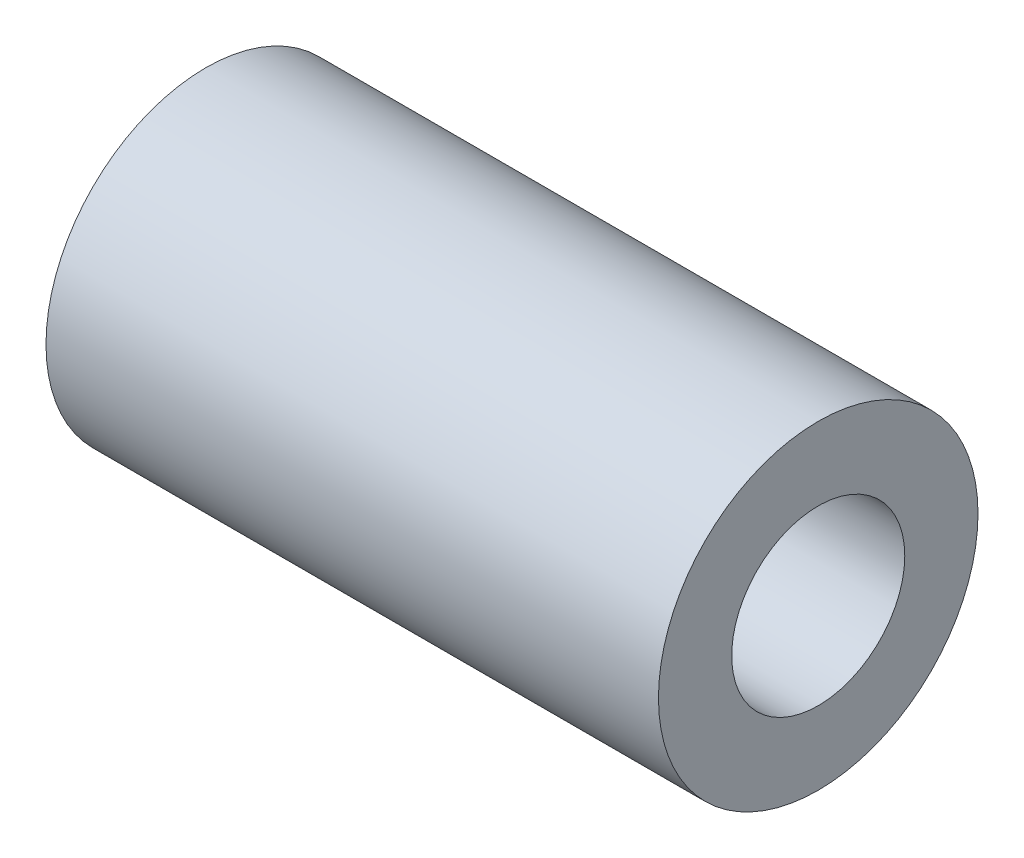
SolidWorks part; units mm, degrees
material "Nylon 101"
ref_plane "Спереди" through (0, 0, 0) normal (0, 0, 1) x (1, 0, 0)
ref_plane "Сверху" through (0, 0, 0) normal (0, 1, 0) x (1, 0, 0)
ref_plane "Справа" through (0, 0, 0) normal (1, 0, 0) x (0, 0, -1)
sketch "Эскиз1" plane through (0, 0, 0) normal (0, 0, 1) x (1, 0, 0)
  line L0 (0, 0) -> (-50000, 0) construction
  line L9 (0, 0) -> (0, 50000) construction
  line L10 (-11.5, 6) -> (11.5, 6)
  line L11 (11.5, 6) -> (11.5, 3.25)
  line L13 (-11.5, 3.25) -> (-11.5, 6)
  line L18 (-11.5, 3.25) -> (11.5, 3.25)
  dimension "D1" = 6.5
  dimension "D2" = 12
  dimension "D3" = 23
revolve "Повернуть1" add sketch "Эскиз1" angle 360 about L0
